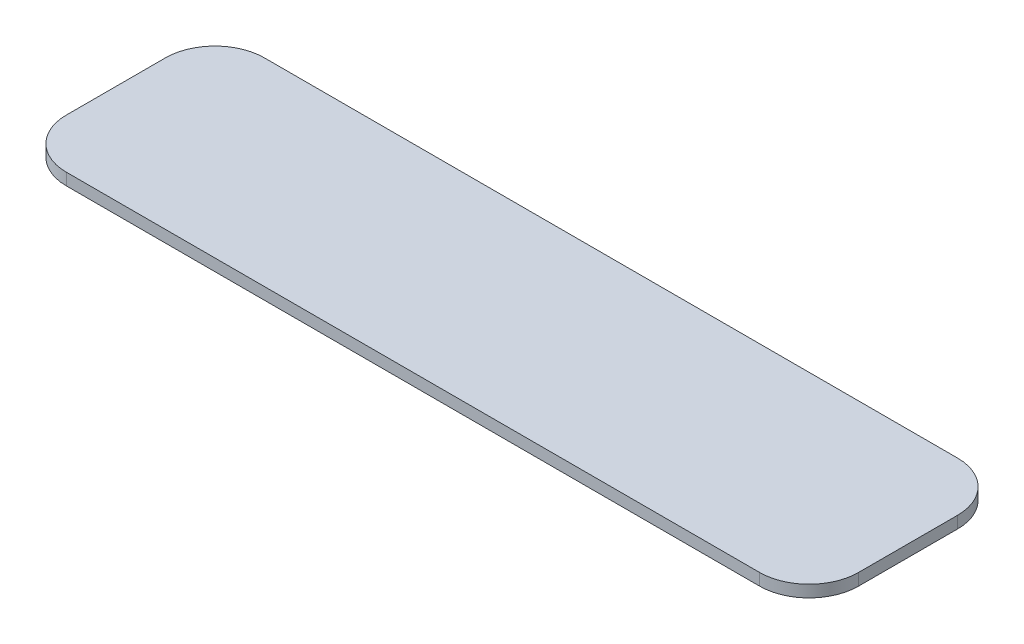
SolidWorks part; units mm, degrees
ref_plane "Front Plane" through (0, 0, 0) normal (0, 0, 1) x (1, 0, 0)
ref_plane "Top Plane" through (0, 0, 0) normal (0, 1, 0) x (1, 0, 0)
ref_plane "Right Plane" through (0, 0, 0) normal (1, 0, 0) x (0, 0, -1)
sketch "Sketch1" plane through (0, 0, 0) normal (0, 1, 0) x (1, 0, 0)
  line L1 (80, -20) -> (-80, -20)
  line L2 (80, -20) -> (80, 20)
  line L3 (80, 20) -> (-80, 20)
  line L4 (-80, -20) -> (-80, 20)
  line L5 (80, -20) -> (-80, 20) construction
  line L6 (80, 20) -> (-80, -20) construction
  point P0 (0, 0)
  dimension "D1" = 160
  dimension "D2" = 40
extrude "Boss-Extrude1" add sketch "Sketch1" along normal mid plane 2.4
fillet "Fillet1" radius 10 4 edges at (-80, 0, 20) (-80, 0, -20) (80, 0, -20) (80, 0, 20)
sketch "Sketch2" plane through (0, 0, 0) normal (0, 1, 0) x (1, 0, 0)
  line L0 (-80, -14.1036) -> (80, -14.1036) construction
  line L1 (-80, 10) -> (-80, -10) construction
  line L2 (80, -10) -> (80, 10) construction
  text T0 "TINSEL" font "Century Gothic" height 30
  dimension "D1" = 15
extrude "Cut-Extrude1" cut sketch "Sketch2" against normal mid plane 0.2
sketch "Sketch3" plane through (0, -0.1, 0) normal (0, 1, 0) x (1, 0, 0)
  line L32 (-72, 13.3195) -> (-65.4615, 13.3195)
  line L33 (-65.4615, 13.3195) -> (-65.4615, -13.6036)
  line L34 (-65.4615, -13.6036) -> (-63.7692, -13.6036)
  line L35 (-63.7692, -13.6036) -> (-63.7692, 13.3195)
  line L36 (-63.7692, 13.3195) -> (-57.2308, 13.3195)
  line L37 (-57.2308, 13.3195) -> (-57.2308, 15.3964)
  line L38 (-57.2308, 15.3964) -> (-72, 15.3964)
  line L39 (-72, 15.3964) -> (-72, 13.3195)
  line L40 (-72, 13.3195) -> (-65.4615, 13.3195)
  line L41 (-65.4615, 13.3195) -> (-65.4615, -13.6036)
  line L42 (-65.4615, -13.6036) -> (-63.7692, -13.6036)
  line L43 (-63.7692, -13.6036) -> (-63.7692, 13.3195)
  line L44 (-63.7692, 13.3195) -> (-57.2308, 13.3195)
  line L45 (-57.2308, 13.3195) -> (-57.2308, 15.3964)
  line L46 (-57.2308, 15.3964) -> (-72, 15.3964)
  line L47 (-72, 15.3964) -> (-72, 13.3195)
  line L48 (-46.5385, 15.3964) -> (-46.5385, -13.6036)
  line L49 (-46.5385, -13.6036) -> (-44.8462, -13.6036)
  line L50 (-44.8462, -13.6036) -> (-44.8462, 15.3964)
  line L51 (-44.8462, 15.3964) -> (-46.5385, 15.3964)
  line L52 (-46.5385, 15.3964) -> (-46.5385, -13.6036)
  line L53 (-46.5385, -13.6036) -> (-44.8462, -13.6036)
  line L54 (-44.8462, -13.6036) -> (-44.8462, 15.3964)
  line L55 (-44.8462, 15.3964) -> (-46.5385, 15.3964)
  line L66 (16.1567, 10.4387) -> (17.806, 11.6889)
  line L67 (3.5569, -7.4816) -> (1.8641, -8.4965)
  line L68 (16.1567, 10.4387) -> (17.806, 11.6889)
  line L69 (3.5569, -7.4816) -> (1.8641, -8.4965)
  line L72 (-31.0769, -13.6036) -> (-29.3846, -13.6036)
  line L73 (-29.3846, -13.6036) -> (-29.3846, 10.8276)
  line L74 (-29.3846, 10.8276) -> (-9, -13.4604)
  line L75 (-9, -13.4604) -> (-9, 15.3964)
  line L76 (-9, 15.3964) -> (-10.6923, 15.3964)
  line L77 (-10.6923, 15.3964) -> (-10.6923, -9.0887)
  line L78 (-10.6923, -9.0887) -> (-31.0769, 15.1961)
  line L79 (-31.0769, 15.1961) -> (-31.0769, -13.6036)
  line L80 (-31.0769, -13.6036) -> (-29.3846, -13.6036)
  line L81 (-29.3846, -13.6036) -> (-29.3846, 10.8276)
  line L82 (-29.3846, 10.8276) -> (-9, -13.4604)
  line L83 (-9, -13.4604) -> (-9, 15.3964)
  line L84 (-9, 15.3964) -> (-10.6923, 15.3964)
  line L85 (-10.6923, 15.3964) -> (-10.6923, -9.0887)
  line L86 (-10.6923, -9.0887) -> (-31.0769, 15.1961)
  line L87 (-31.0769, 15.1961) -> (-31.0769, -13.6036)
  line L108 (30.6154, 15.3964) -> (30.6154, -13.6036)
  line L109 (30.6154, -13.6036) -> (46.5385, -13.6036)
  line L110 (46.5385, -13.6036) -> (46.5385, -11.5266)
  line L111 (46.5385, -11.5266) -> (32.3077, -11.5266)
  line L112 (32.3077, -11.5266) -> (32.3077, 1.0118)
  line L113 (32.3077, 1.0118) -> (46.5385, 1.0118)
  line L114 (46.5385, 1.0118) -> (46.5385, 3.0888)
  line L115 (46.5385, 3.0888) -> (32.3077, 3.0888)
  line L116 (32.3077, 3.0888) -> (32.3077, 13.3195)
  line L117 (32.3077, 13.3195) -> (46.5385, 13.3195)
  line L118 (46.5385, 13.3195) -> (46.5385, 15.3964)
  line L119 (46.5385, 15.3964) -> (30.6154, 15.3964)
  line L120 (30.6154, 15.3964) -> (30.6154, -13.6036)
  line L121 (30.6154, -13.6036) -> (46.5385, -13.6036)
  line L122 (46.5385, -13.6036) -> (46.5385, -11.5266)
  line L123 (46.5385, -11.5266) -> (32.3077, -11.5266)
  line L124 (32.3077, -11.5266) -> (32.3077, 1.0118)
  line L125 (32.3077, 1.0118) -> (46.5385, 1.0118)
  line L126 (46.5385, 1.0118) -> (46.5385, 3.0888)
  line L127 (46.5385, 3.0888) -> (32.3077, 3.0888)
  line L128 (32.3077, 3.0888) -> (32.3077, 13.3195)
  line L129 (32.3077, 13.3195) -> (46.5385, 13.3195)
  line L130 (46.5385, 13.3195) -> (46.5385, 15.3964)
  line L131 (46.5385, 15.3964) -> (30.6154, 15.3964)
  line L132 (58, 15.3964) -> (58, -13.6036)
  line L133 (58, -13.6036) -> (71.2308, -13.6036)
  line L134 (71.2308, -13.6036) -> (71.2308, -11.5266)
  line L135 (71.2308, -11.5266) -> (59.6923, -11.5266)
  line L136 (59.6923, -11.5266) -> (59.6923, 15.3964)
  line L137 (59.6923, 15.3964) -> (58, 15.3964)
  line L138 (58, 15.3964) -> (58, -13.6036)
  line L139 (58, -13.6036) -> (71.2308, -13.6036)
  line L140 (71.2308, -13.6036) -> (71.2308, -11.5266)
  line L141 (71.2308, -11.5266) -> (59.6923, -11.5266)
  line L142 (59.6923, -11.5266) -> (59.6923, 15.3964)
  line L143 (59.6923, 15.3964) -> (58, 15.3964)
  spline S30 degree 3 poles (-2469.7541, -1706.2239) (91.4523, 152.4343) (-20.7285, 20.1) (3.6195, -11.1159) (3.9112, -11.4597) (4.3881, -11.946) (4.5533, -12.1044) (4.8907, -12.4101) (5.0638, -12.5563) (5.6022, -12.9673) (5.9844, -13.2072) (6.5851, -13.5264) (6.7917, -13.6255) (7.2108, -13.8035) (7.423, -13.8824) (7.8517, -14.0239) (8.0679, -14.088) (8.5058, -14.195) (8.7281, -14.2356) (9.1767, -14.3024) (9.4031, -14.3304) (24.0565, -15.4076) (40.7882, 33.0707) (-86.497, -3012.466) knots -10.621374 -10.621374 -10.621374 -10.621374 0.25 0.25 0.375 0.375 0.4375 0.4375 0.5 0.5 0.625 0.625 0.6875 0.6875 0.75 0.75 0.8125 0.8125 0.875 0.875 0.9375 0.9375 4.899763 4.899763 4.899763 4.899763 only from (1.8641, -8.4965) to (10.3144, -14.3727)
  spline S31 degree 3 poles (458.525, -2980.3349) (-29.1384, 33.2831) (-4.8545, -15.4854) (11.3414, -14.3251) (11.5947, -14.2926) (12.0973, -14.2043) (12.3468, -14.1487) (12.8417, -14.0138) (13.0883, -13.9339) (13.8133, -13.6586) (14.2702, -13.4308) (14.9148, -13.0209) (15.1225, -12.8724) (15.5267, -12.5564) (15.7243, -12.3885) (16.2924, -11.8637) (16.6375, -11.4856) (17.0993, -10.8717) (17.2453, -10.6604) (17.5141, -10.2183) (17.6333, -9.9887) (17.8468, -9.5227) (17.9438, -9.2861) (18.1075, -8.8014) (18.1722, -8.5528) (18.2798, -8.0472) (18.3237, -7.7914) (19.7062, 6.4577) (-36.8699, 25.761) (3009.1002, -239.3494) knots -3.834294 -3.834294 -3.834294 -3.834294 0.0625 0.0625 0.125 0.125 0.1875 0.1875 0.25 0.25 0.375 0.375 0.4375 0.4375 0.5 0.5 0.625 0.625 0.6875 0.6875 0.75 0.75 0.8125 0.8125 0.875 0.875 0.9375 0.9375 4.344957 4.344957 4.344957 4.344957 only from (10.3144, -14.3727) to (18.3843, -6.7613)
  spline S32 degree 3 poles (2953.2559, 612.8232) (-26.996, -48.7102) (19.9127, -21.849) (18.3095, -5.767) (18.2705, -5.523) (18.1593, -5.0427) (18.0891, -4.8058) (17.9274, -4.3369) (17.8354, -4.105) (17.5257, -3.417) (17.2791, -2.983) (16.8678, -2.3593) (16.7241, -2.1556) (16.4179, -1.7603) (16.2548, -1.5684) (15.7532, -1.0069) (15.4005, -0.6515) (14.6708, 0.0346) (14.2958, 0.3677) (13.5275, 1.0132) (13.1347, 1.3247) (-14.2374, 22.1301) (-69.9987, 5.3158) (1763.0344, 2436.8279) knots -3.940733 -3.940733 -3.940733 -3.940733 0.0625 0.0625 0.125 0.125 0.1875 0.1875 0.25 0.25 0.375 0.375 0.4375 0.4375 0.5 0.5 0.625 0.625 0.75 0.75 0.875 0.875 9.323121 9.323121 9.323121 9.323121 only from (18.3843, -6.7613) to (11.5256, 2.5216)
  spline S33 degree 3 poles (-1596.9722, -2526.888) (113.6624, -34.5012) (53.5368, -27.6073) (10.1458, 3.506) (9.8005, 3.7517) (9.113, 4.2471) (8.7738, 4.5009) (8.2666, 4.8835) (8.0963, 5.0096) (7.8459, 5.2051) (7.7634, 5.2714) (-0.5289, 12.2685) (9.826, 43.2384) (-1851.0095, -2348.7754) knots -31.001318 -31.001318 -31.001318 -31.001318 0.25 0.25 0.5 0.5 0.75 0.75 0.875 0.875 0.9375 0.9375 7.273259 7.273259 7.273259 7.273259 only from (11.5256, 2.5216) to (7.443, 5.5494)
  spline S34 degree 3 poles (-2134.283, -2094.5957) (86.1673, 30.4355) (18.5691, -7.8589) (6.3334, 6.7552) (6.0975, 7.0868) (5.8062, 7.6192) (5.7194, 7.8025) (5.5708, 8.1835) (5.5108, 8.3826) (5.4129, 8.7811) (5.3697, 8.9813) (3.9304, 20.0299) (63.521, 40.6366) (-2961.6332, -432.3398) knots -11.11166 -11.11166 -11.11166 -11.11166 0.25 0.25 0.5 0.5 0.625 0.625 0.75 0.75 0.875 0.875 7.557656 7.557656 7.557656 7.557656 only from (7.443, 5.5494) to (5.3074, 9.7997)
  spline S35 degree 3 poles (-2940.9028, 573.9105) (76.4529, -29.92) (2.8334, -1.8233) (5.4334, 10.8436) (5.473, 10.9883) (5.5705, 11.274) (5.629, 11.416) (5.8278, 11.8275) (5.9898, 12.0807) (6.3682, 12.5484) (6.5866, 12.765) (7.0532, 13.1531) (7.3026, 13.3247) (7.8385, 13.6158) (8.12, 13.7337) (8.6947, 13.9208) (8.9915, 13.99) (23.8431, 15.9138) (43.3306, -48.8628) (-168.493, 3008.4532) knots -5.211055 -5.211055 -5.211055 -5.211055 0.125 0.125 0.1875 0.1875 0.25 0.25 0.375 0.375 0.5 0.5 0.625 0.625 0.75 0.75 0.875 0.875 6.875879 6.875879 6.875879 6.875879 only from (5.3074, 9.7997) to (10.208, 14.0891)
  spline S36 degree 3 poles (527.4837, 2968.8023) (-30.283, -49.34) (-3.1972, 16.0231) (11.4092, 13.9818) (11.702, 13.9152) (12.2789, 13.7363) (12.5651, 13.6218) (13.1069, 13.3529) (13.3651, 13.1988) (13.8565, 12.8518) (14.0902, 12.6598) (14.5409, 12.2497) (14.7553, 12.0346) (15.178, 11.5991) (15.3792, 11.3719) (34.2751, -10.7235) (25.945, -57.2747) (-2139.9517, -2074.4154) knots -5.886787 -5.886787 -5.886787 -5.886787 0.125 0.125 0.25 0.25 0.375 0.375 0.5 0.5 0.625 0.625 0.75 0.75 0.875 0.875 12.723279 12.723279 12.723279 12.723279 only from (10.208, 14.0891) to (16.1567, 10.4387)
  spline S37 degree 3 poles (-2086.531, -2120.3763) (-284.1913, -467.4685) (71.1463, -52.3603) (16.8793, 12.8515) (16.6356, 13.1319) (16.1274, 13.6749) (15.8606, 13.9364) (15.3071, 14.4292) (15.0208, 14.6625) (14.4121, 15.0803) (14.0885, 15.2649) (13.4136, 15.589) (13.0687, 15.7261) (12.363, 15.9488) (12.0024, 16.0345) (-4.4908, 18.3578) (-33.0097, -52.7314) (615.1738, 2954.1273) knots -28.295663 -28.295663 -28.295663 -28.295663 0.125 0.125 0.25 0.25 0.375 0.375 0.5 0.5 0.625 0.625 0.75 0.75 0.875 0.875 6.30996 6.30996 6.30996 6.30996 only from (17.806, 11.6889) to (10.5079, 16.1654)
  spline S38 degree 3 poles (-476.6821, 2976.0165) (50.5516, -22.9072) (26.4444, 17.3094) (9.6269, 16.1177) (9.4088, 16.0938) (8.7608, 15.9877) (8.337, 15.8722) (7.5031, 15.5646) (7.1003, 15.378) (6.533, 15.0401) (6.3491, 14.9185) (5.9901, 14.6601) (5.814, 14.5218) (5.3196, 14.0795) (5.036, 13.7468) (4.6513, 13.2139) (4.5315, 13.0294) (4.3128, 12.643) (4.2151, 12.444) (3.9569, 11.8369) (3.8277, 11.417) (3.6972, 10.765) (3.6669, 10.5448) (2.437, -4.6496) (47.4006, -23.6338) (-2988.3213, 224.9458) knots -4.661718 -4.661718 -4.661718 -4.661718 0.0625 0.0625 0.125 0.125 0.25 0.25 0.375 0.375 0.4375 0.4375 0.5 0.5 0.625 0.625 0.6875 0.6875 0.75 0.75 0.875 0.875 0.9375 0.9375 5.180781 5.180781 5.180781 5.180781 only from (10.5079, 16.1654) to (3.6156, 9.6608)
  spline S39 degree 3 poles (-2983.8888, -260.8062) (49.9911, 38.9302) (2.6338, 21.5169) (3.6546, 8.8893) (3.6815, 8.6982) (3.7512, 8.3176) (3.7945, 8.1282) (3.9012, 7.7591) (3.9639, 7.5784) (4.0987, 7.2208) (4.1718, 7.0443) (4.3369, 6.699) (4.4283, 6.5299) (4.6248, 6.1974) (4.73, 6.0344) (13.5145, -6.5325) (55.0776, 4.0671) (-2426.8127, -1750.6379) knots -7.95922 -7.95922 -7.95922 -7.95922 0.125 0.125 0.25 0.25 0.375 0.375 0.5 0.5 0.625 0.625 0.75 0.75 0.875 0.875 10.662449 10.662449 10.662449 10.662449 only from (3.6156, 9.6608) to (5.1839, 5.408)
  spline S40 degree 3 poles (-2138.8592, -2092.3927) (13.4931, 47.2182) (-2.5756, 14.0987) (5.5256, 5.0127) (5.6155, 4.9184) (5.8922, 4.6424) (6.0864, 4.4681) (6.6761, 3.9525) (7.0798, 3.6208) (7.8995, 2.9733) (8.3142, 2.6556) (36.8216, -18.7069) (95.9082, 1.9702) (-1693.9623, -2466.3) knots -5.705274 -5.705274 -5.705274 -5.705274 0.0625 0.0625 0.125 0.125 0.25 0.25 0.5 0.5 0.75 0.75 17.55356 17.55356 17.55356 17.55356 only from (5.1839, 5.408) to (10.0002, 1.4223)
  spline S41 degree 3 poles (1701.438, 2477.7365) (-77.5273, -1.4221) (-16.6075, 21.7693) (11.9848, -0.0495) (12.4635, -0.4396) (13.409, -1.2348) (13.862, -1.6522) (14.5191, -2.2999) (14.732, -2.5216) (26.9331, -16.4278) (-2.2156, -70.2694) (2199.0575, 2053.2038) knots -14.054738 -14.054738 -14.054738 -14.054738 0.25 0.25 0.5 0.5 0.75 0.75 0.875 0.875 8.260362 8.260362 8.260362 8.260362 only from (10.0002, 1.4223) to (15.52, -3.4712)
  spline S42 degree 3 poles (2510.4263, 1661.9428) (-51.2437, -11.7658) (8.4754, 8.8807) (16.1452, -4.4646) (16.27, -4.7298) (16.4788, -5.2787) (16.5617, -5.5583) (18.8864, -18.6465) (-50.271, -44.4189) (2974.7225, 491.579) knots -12.596307 -12.596307 -12.596307 -12.596307 0.25 0.25 0.5 0.5 0.75 0.75 11.986005 11.986005 11.986005 11.986005 only from (15.52, -3.4712) to (16.6929, -6.7107)
  spline S43 degree 3 poles (2975.176, -502.621) (-26.8461, 26.7198) (17.9456, 5.548) (16.6357, -7.4918) (16.6048, -7.684) (16.4739, -8.2539) (16.3309, -8.6275) (15.988, -9.3324) (15.783, -9.6649) (15.4136, -10.1271) (15.28, -10.2752) (15.0009, -10.5531) (14.8549, -10.6841) (14.5509, -10.9317) (14.3927, -11.048) (14.063, -11.2643) (13.8909, -11.3647) (13.368, -11.6417) (13.009, -11.7988) (12.4516, -11.985) (12.2628, -12.0391) (11.88, -12.1335) (11.6854, -12.1743) (11.2951, -12.2377) (11.0989, -12.2594) (-3.6564, -13.2309) (-22.1613, 27.2455) (251.7339, -3002.2406) knots -4.069059 -4.069059 -4.069059 -4.069059 0.0625 0.0625 0.125 0.125 0.25 0.25 0.375 0.375 0.4375 0.4375 0.5 0.5 0.5625 0.5625 0.625 0.625 0.75 0.75 0.8125 0.8125 0.875 0.875 0.9375 0.9375 5.5575 5.5575 5.5575 5.5575 only from (16.6929, -6.7107) to (10.3097, -12.2962)
  spline S44 degree 3 poles (-565.5279, -2956.2153) (55.2698, 60.1047) (24.0681, -14.8359) (8.8753, -12.1338) (8.5296, -12.0323) (8.0203, -11.8361) (7.8514, -11.7627) (7.5234, -11.6033) (7.3637, -11.517) (6.8964, -11.2398) (6.6005, -11.0311) (6.0331, -10.5758) (5.7621, -10.3285) (5.2548, -9.8123) (5.0163, -9.542) (4.5622, -8.9831) (4.3468, -8.6943) (-10.0334, 12.229) (32.8595, 78.6177) (-2381.835, -1825.7167) knots -5.11651 -5.11651 -5.11651 -5.11651 0.125 0.125 0.25 0.25 0.3125 0.3125 0.375 0.375 0.5 0.5 0.625 0.625 0.75 0.75 0.875 0.875 9.540048 9.540048 9.540048 9.540048 only from (10.3097, -12.2962) to (3.5569, -7.4816)
  spline S45 degree 3 poles (1.8641, -8.4965) (2.3077, -9.2881) (2.7892, -10.0514) (3.6195, -11.1159) (3.9112, -11.4597) (4.3881, -11.946) (4.5533, -12.1044) (4.8907, -12.4101) (5.0638, -12.5563) (5.6022, -12.9673) (5.9844, -13.2072) (6.5851, -13.5264) (6.7917, -13.6255) (7.2108, -13.8035) (7.423, -13.8824) (7.8517, -14.0239) (8.0679, -14.088) (8.5058, -14.195) (8.7281, -14.2356) (9.1767, -14.3024) (9.4031, -14.3304) (9.8582, -14.3639) (10.0863, -14.3683) (10.3144, -14.3727) knots 0 0 0 0 0.25 0.25 0.375 0.375 0.4375 0.4375 0.5 0.5 0.625 0.625 0.6875 0.6875 0.75 0.75 0.8125 0.8125 0.875 0.875 0.9375 0.9375 1 1 1 1
  spline S46 degree 3 poles (10.3144, -14.3727) (10.5722, -14.3672) (10.83, -14.3617) (11.3414, -14.3251) (11.5947, -14.2926) (12.0973, -14.2043) (12.3468, -14.1487) (12.8417, -14.0138) (13.0883, -13.9339) (13.8133, -13.6586) (14.2702, -13.4308) (14.9148, -13.0209) (15.1225, -12.8724) (15.5267, -12.5564) (15.7243, -12.3885) (16.2924, -11.8637) (16.6375, -11.4856) (17.0993, -10.8717) (17.2453, -10.6604) (17.5141, -10.2183) (17.6333, -9.9887) (17.8468, -9.5227) (17.9438, -9.2861) (18.1075, -8.8014) (18.1722, -8.5528) (18.2798, -8.0472) (18.3237, -7.7914) (18.3735, -7.2781) (18.3789, -7.0197) (18.3843, -6.7613) knots 0 0 0 0 0.0625 0.0625 0.125 0.125 0.1875 0.1875 0.25 0.25 0.375 0.375 0.4375 0.4375 0.5 0.5 0.625 0.625 0.6875 0.6875 0.75 0.75 0.8125 0.8125 0.875 0.875 0.9375 0.9375 1 1 1 1
  spline S47 degree 3 poles (18.3843, -6.7613) (18.3716, -6.5113) (18.3588, -6.2614) (18.3095, -5.767) (18.2705, -5.523) (18.1593, -5.0427) (18.0891, -4.8058) (17.9274, -4.3369) (17.8354, -4.105) (17.5257, -3.417) (17.2791, -2.983) (16.8678, -2.3593) (16.7241, -2.1556) (16.4179, -1.7603) (16.2548, -1.5684) (15.7532, -1.0069) (15.4005, -0.6515) (14.6708, 0.0346) (14.2958, 0.3677) (13.5275, 1.0132) (13.1347, 1.3247) (12.3365, 1.9314) (11.9311, 2.2266) (11.5256, 2.5216) knots 0 0 0 0 0.0625 0.0625 0.125 0.125 0.1875 0.1875 0.25 0.25 0.375 0.375 0.4375 0.4375 0.5 0.5 0.625 0.625 0.75 0.75 0.875 0.875 1 1 1 1
  spline S48 degree 3 poles (11.5256, 2.5216) (11.1799, 2.7668) (10.8345, 3.0121) (10.1458, 3.506) (9.8005, 3.7517) (9.113, 4.2471) (8.7738, 4.5009) (8.2666, 4.8835) (8.0963, 5.0096) (7.8459, 5.2051) (7.7634, 5.2714) (7.6014, 5.4081) (7.5222, 5.4788) (7.443, 5.5494) knots 0 0 0 0 0.25 0.25 0.5 0.5 0.75 0.75 0.875 0.875 0.9375 0.9375 1 1 1 1
  spline S49 degree 3 poles (7.443, 5.5494) (7.1506, 5.8368) (6.8603, 6.1259) (6.3334, 6.7552) (6.0975, 7.0868) (5.8062, 7.6192) (5.7194, 7.8025) (5.5708, 8.1835) (5.5108, 8.3826) (5.4129, 8.7811) (5.3697, 8.9813) (5.3168, 9.3871) (5.3117, 9.5933) (5.3074, 9.7997) knots 0 0 0 0 0.25 0.25 0.5 0.5 0.625 0.625 0.75 0.75 0.875 0.875 1 1 1 1
  spline S50 degree 3 poles (5.3074, 9.7997) (5.3247, 10.1018) (5.3431, 10.4037) (5.4334, 10.8436) (5.473, 10.9883) (5.5705, 11.274) (5.629, 11.416) (5.8278, 11.8275) (5.9898, 12.0807) (6.3682, 12.5484) (6.5866, 12.765) (7.0532, 13.1531) (7.3026, 13.3247) (7.8385, 13.6158) (8.12, 13.7337) (8.6947, 13.9208) (8.9915, 13.99) (9.5976, 14.0685) (9.9028, 14.0789) (10.208, 14.0891) knots 0 0 0 0 0.125 0.125 0.1875 0.1875 0.25 0.25 0.375 0.375 0.5 0.5 0.625 0.625 0.75 0.75 0.875 0.875 1 1 1 1
  spline S51 degree 3 poles (10.208, 14.0891) (10.5112, 14.0774) (10.8142, 14.065) (11.4092, 13.9818) (11.702, 13.9152) (12.2789, 13.7363) (12.5651, 13.6218) (13.1069, 13.3529) (13.3651, 13.1988) (13.8565, 12.8518) (14.0902, 12.6598) (14.5409, 12.2497) (14.7553, 12.0346) (15.178, 11.5991) (15.3792, 11.3719) (15.7737, 10.9106) (15.968, 10.6772) (16.1567, 10.4387) knots 0 0 0 0 0.125 0.125 0.25 0.25 0.375 0.375 0.5 0.5 0.625 0.625 0.75 0.75 0.875 0.875 1 1 1 1
  spline S52 degree 3 poles (17.806, 11.6889) (17.5843, 11.9881) (17.3546, 12.2804) (16.8793, 12.8515) (16.6356, 13.1319) (16.1274, 13.6749) (15.8606, 13.9364) (15.3071, 14.4292) (15.0208, 14.6625) (14.4121, 15.0803) (14.0885, 15.2649) (13.4136, 15.589) (13.0687, 15.7261) (12.363, 15.9488) (12.0024, 16.0345) (11.2608, 16.139) (10.8834, 16.1524) (10.5079, 16.1654) knots 0 0 0 0 0.125 0.125 0.25 0.25 0.375 0.375 0.5 0.5 0.625 0.625 0.75 0.75 0.875 0.875 1 1 1 1
  spline S53 degree 3 poles (10.5079, 16.1654) (10.2869, 16.1572) (10.066, 16.1488) (9.6269, 16.1177) (9.4088, 16.0938) (8.7608, 15.9877) (8.337, 15.8722) (7.5031, 15.5646) (7.1003, 15.378) (6.533, 15.0401) (6.3491, 14.9185) (5.9901, 14.6601) (5.814, 14.5218) (5.3196, 14.0795) (5.036, 13.7468) (4.6513, 13.2139) (4.5315, 13.0294) (4.3128, 12.643) (4.2151, 12.444) (3.9569, 11.8369) (3.8277, 11.417) (3.6972, 10.765) (3.6669, 10.5448) (3.6312, 10.1037) (3.6234, 9.8822) (3.6156, 9.6608) knots 0 0 0 0 0.0625 0.0625 0.125 0.125 0.25 0.25 0.375 0.375 0.4375 0.4375 0.5 0.5 0.625 0.625 0.6875 0.6875 0.75 0.75 0.875 0.875 0.9375 0.9375 1 1 1 1
  spline S54 degree 3 poles (3.6156, 9.6608) (3.6196, 9.4673) (3.6235, 9.2739) (3.6546, 8.8893) (3.6815, 8.6982) (3.7512, 8.3176) (3.7945, 8.1282) (3.9012, 7.7591) (3.9639, 7.5784) (4.0987, 7.2208) (4.1718, 7.0443) (4.3369, 6.699) (4.4283, 6.5299) (4.6248, 6.1974) (4.73, 6.0344) (4.9516, 5.7175) (5.0677, 5.5627) (5.1839, 5.408) knots 0 0 0 0 0.125 0.125 0.25 0.25 0.375 0.375 0.5 0.5 0.625 0.625 0.75 0.75 0.875 0.875 1 1 1 1
  spline S55 degree 3 poles (5.1839, 5.408) (5.2679, 5.3078) (5.3519, 5.2075) (5.5256, 5.0127) (5.6155, 4.9184) (5.8922, 4.6424) (6.0864, 4.4681) (6.6761, 3.9525) (7.0798, 3.6208) (7.8995, 2.9733) (8.3142, 2.6556) (9.15, 2.0293) (9.5748, 1.7253) (10.0002, 1.4223) knots 0 0 0 0 0.0625 0.0625 0.125 0.125 0.25 0.25 0.5 0.5 0.75 0.75 1 1 1 1
  spline S56 degree 3 poles (10.0002, 1.4223) (10.5014, 1.0612) (11.0025, 0.7001) (11.9848, -0.0495) (12.4635, -0.4396) (13.409, -1.2348) (13.862, -1.6522) (14.5191, -2.2999) (14.732, -2.5216) (15.1382, -2.9845) (15.3295, -3.2275) (15.52, -3.4712) knots 0 0 0 0 0.25 0.25 0.5 0.5 0.75 0.75 0.875 0.875 1 1 1 1
  spline S57 degree 3 poles (15.52, -3.4712) (15.6862, -3.7131) (15.8524, -3.9551) (16.1452, -4.4646) (16.27, -4.7298) (16.4788, -5.2787) (16.5617, -5.5583) (16.6629, -6.128) (16.6782, -6.4193) (16.6929, -6.7107) knots 0 0 0 0 0.25 0.25 0.5 0.5 0.75 0.75 1 1 1 1
  spline S58 degree 3 poles (16.6929, -6.7107) (16.6838, -6.9069) (16.6748, -7.1031) (16.6357, -7.4918) (16.6048, -7.684) (16.4739, -8.2539) (16.3309, -8.6275) (15.988, -9.3324) (15.783, -9.6649) (15.4136, -10.1271) (15.28, -10.2752) (15.0009, -10.5531) (14.8549, -10.6841) (14.5509, -10.9317) (14.3927, -11.048) (14.063, -11.2643) (13.8909, -11.3647) (13.368, -11.6417) (13.009, -11.7988) (12.4516, -11.985) (12.2628, -12.0391) (11.88, -12.1335) (11.6854, -12.1743) (11.2951, -12.2377) (11.0989, -12.2594) (10.705, -12.2853) (10.5074, -12.2907) (10.3097, -12.2962) knots 0 0 0 0 0.0625 0.0625 0.125 0.125 0.25 0.25 0.375 0.375 0.4375 0.4375 0.5 0.5 0.5625 0.5625 0.625 0.625 0.75 0.75 0.8125 0.8125 0.875 0.875 0.9375 0.9375 1 1 1 1
  spline S59 degree 3 poles (10.3097, -12.2962) (9.9463, -12.2785) (9.5831, -12.2597) (8.8753, -12.1338) (8.5296, -12.0323) (8.0203, -11.8361) (7.8514, -11.7627) (7.5234, -11.6033) (7.3637, -11.517) (6.8964, -11.2398) (6.6005, -11.0311) (6.0331, -10.5758) (5.7621, -10.3285) (5.2548, -9.8123) (5.0163, -9.542) (4.5622, -8.9831) (4.3468, -8.6943) (3.9378, -8.0992) (3.7452, -7.7922) (3.5569, -7.4816) knots 0 0 0 0 0.125 0.125 0.25 0.25 0.3125 0.3125 0.375 0.375 0.5 0.5 0.625 0.625 0.75 0.75 0.875 0.875 1 1 1 1
  dimension "D1" = 0.5
  dimension "D2" = 0.5
  dimension "D3" = 0.5
  dimension "D4" = 0.5
  dimension "D5" = 0.5
  dimension "D6" = 0.5
extrude "Boss-Extrude2" [suppressed] add sketch "Sketch3" along normal up to next
